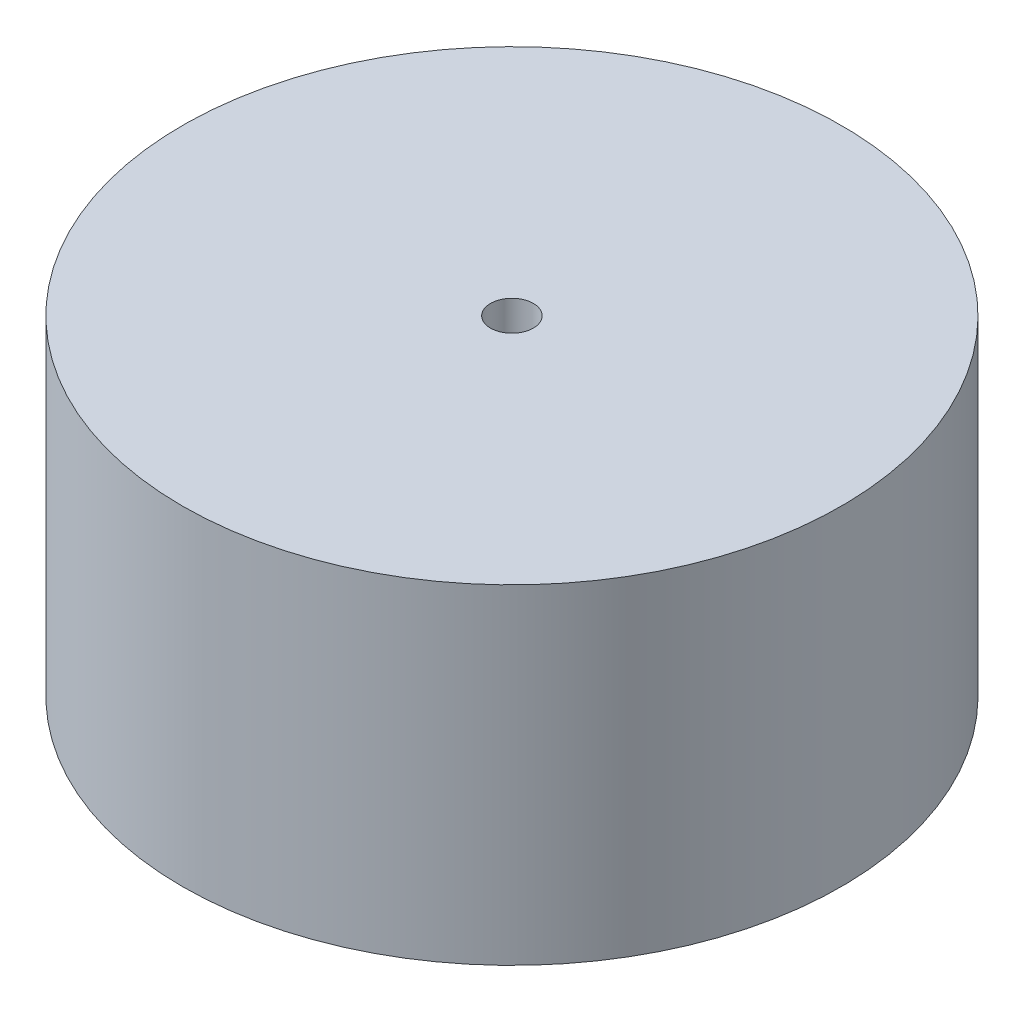
SolidWorks part; units mm, degrees
ref_plane "Front Plane" through (0, 0, 0) normal (0, 0, 1) x (1, 0, 0)
ref_plane "Top Plane" through (0, 0, 0) normal (0, 1, 0) x (1, 0, 0)
ref_plane "Right Plane" through (0, 0, 0) normal (1, 0, 0) x (0, 0, -1)
sketch "Sketch1" plane through (0, 0, 0) normal (0, 1, 0) x (1, 0, 0)
  circle A0 centre (0, 0) radius 10
  dimension "D1" = 20
extrude "Boss-Extrude1" add sketch "Sketch1" along normal blind 10
sketch "Sketch2" plane through (0, 10, 0) normal (0, 1, 0) x (1, 0, 0)
  circle A0 centre (0, 0) radius 0.65
  dimension "D1" = 1.3
extrude "Cut-Extrude1" cut sketch "Sketch2" against normal blind 10
